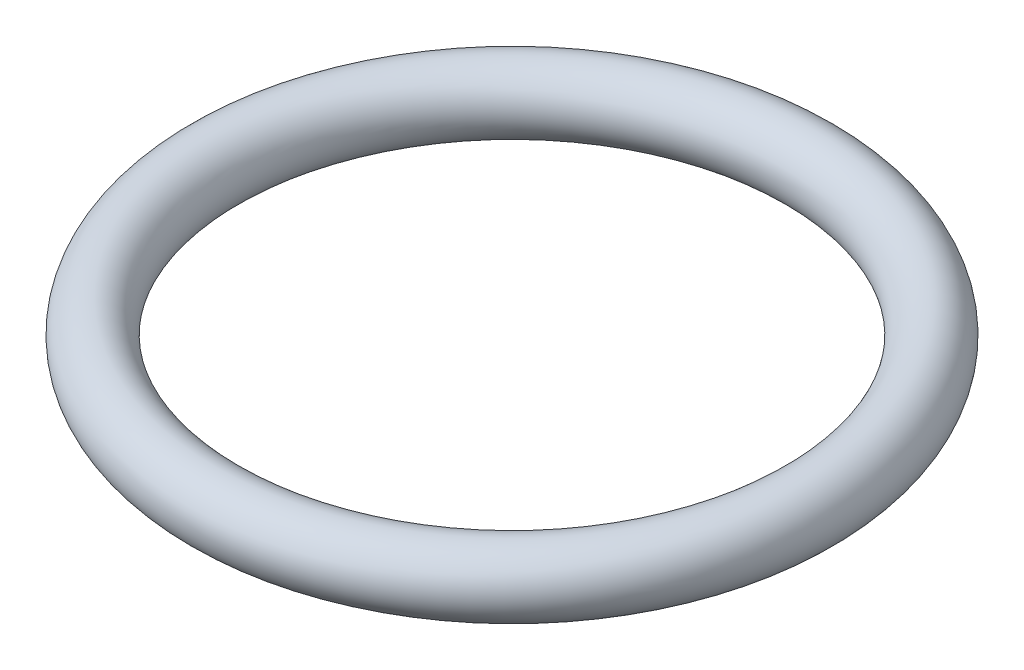
SolidWorks part; units mm, degrees
material "Silikon Kauçuk"
ref_plane "Ön Düzlem" through (0, 0, 0) normal (0, 0, 1) x (1, 0, 0)
ref_plane "Üst Düzlem" through (0, 0, 0) normal (0, 1, 0) x (1, 0, 0)
ref_plane "Sağ Düzlem" through (0, 0, 0) normal (1, 0, 0) x (0, 0, -1)
sketch "Çizim2" plane through (0, 0, 0) normal (0, 1, 0) x (1, 0, 0)
  line L0 (0, 0) -> (20, 0)
  circle A0 centre (0, 0) radius 20
  dimension "D1" = 40
sketch "Çizim3" plane through (0, 0, 0) normal (0, 0, 1) x (1, 0, 0)
  circle A1 centre (22.5, 0) radius 2.5
  dimension "D2" = 5
sweep "Süpür1" add profiles "Çizim3" path "Çizim2"
